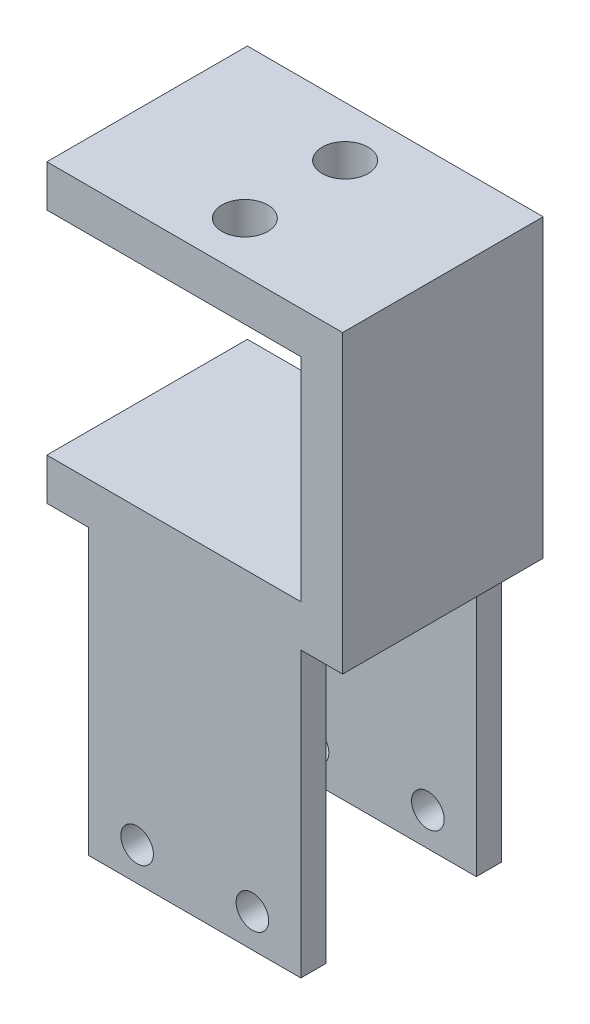
SolidWorks part; units mm, degrees
ref_plane "Front Plane" through (0, 0, 0) normal (0, 0, 1) x (1, 0, 0)
ref_plane "Top Plane" through (0, 0, 0) normal (0, 1, 0) x (1, 0, 0)
ref_plane "Right Plane" through (0, 0, 0) normal (1, 0, 0) x (0, 0, -1)
sketch "Sketch1" plane through (0, 0, 0) normal (0, 0, 1) x (1, 0, 0)
  line L2 (0, 0) -> (0, 35.4)
  line L3 (0, 35.4) -> (-35.4, 35.4)
  line L4 (-35.4, 0) -> (-35.4, 35.4)
  line L5 (-30.4, 30.4) -> (-5, 30.4)
  line L6 (-30.4, 30.4) -> (-30.4, 5)
  line L7 (-30.4, 5) -> (-5, 5)
  line L8 (-5, 30.4) -> (-5, 5)
  line L9 (-24.6, -30) -> (-10.8, -30) construction
  line L13 (-30.4, -34) -> (-5, -34)
  line L18 (-35.4, 0) -> (-30.4, 0)
  line L19 (-30.4, -34) -> (-30.4, 0)
  line L20 (0, 0) -> (-5, 0)
  line L23 (-5, 0) -> (-5, -34)
  circle A0 centre (-24.6, -30) radius 1.95
  circle A1 centre (-10.8, -30) radius 1.95
  point P15 (-17.7, -30)
  point P16 (-17.7, 5)
  dimension "D8" = 3.9
  dimension "D9" = 3.9
  dimension "D1" = 35.4
  dimension "D2" = 35.4
  dimension "D3" = 5
  dimension "D4" = 25.4
  dimension "D5" = 5
  dimension "D6" = 25.4
  dimension "D7" = 34
  dimension "D10" = 13.8
  dimension "D11" = 4
extrude "Boss-Extrude1" add sketch "Sketch1" along normal blind 24
sketch "Sketch3" plane through (-35.4, 0, 0) normal (-1, 0, 0) x (0, 0, 1)
  line L0 (24, -34) -> (0, -34) construction
  line L1 (3, -34) -> (21, -34)
  line L2 (3, -34) -> (3, 0)
  line L3 (3, 0) -> (21, 0)
  line L4 (21, -34) -> (21, 0)
  line L5 (0, 35.4) -> (0, 0) construction
  line L6 (24, 35.4) -> (24, 0) construction
  dimension "D1" = 3
  dimension "D2" = 3
extrude "Cut-Extrude1" cut sketch "Sketch3" against normal through all
sketch "Sketch4" plane through (0, 35.4, 0) normal (0, 1, 0) x (1, 0, 0)
  line L0 (-35.4, -24) -> (-35.4, 0) construction
  line L2 (0, 0) -> (-35.4, 0) construction
  line L3 (0, -24) -> (-35.4, -24) construction
  circle A2 centre (-17.7, -6) radius 2.75
  circle A3 centre (-17.7, -18) radius 2.75
  point P4 (0, 0)
  point P7 (-35.4, -12)
  point P8 (0, 0)
  point P11 (-17.7, 0)
  point P12 (0, 0)
  dimension "D3" = 5.5
  dimension "D4" = 5.5
  dimension "D1" = 6
  dimension "D2" = 6
extrude "Cut-Extrude2" cut sketch "Sketch4" against normal up to next
sketch "Sketch5" plane through (0, 0, 0) normal (0, 0, -1) x (-1, 0, 0)
  line L0 (35.4, 35.4) -> (35.4, 0) construction
  line L1 (30.4, 5) -> (35.4, 5)
  line L2 (30.4, 5) -> (30.4, 30.4)
  line L3 (30.4, 30.4) -> (35.4, 30.4)
  line L4 (35.4, 5) -> (35.4, 30.4)
  line L5 (5, 30.4) -> (30.4, 30.4) construction
extrude "Cut-Extrude3" cut sketch "Sketch5" against normal through all
